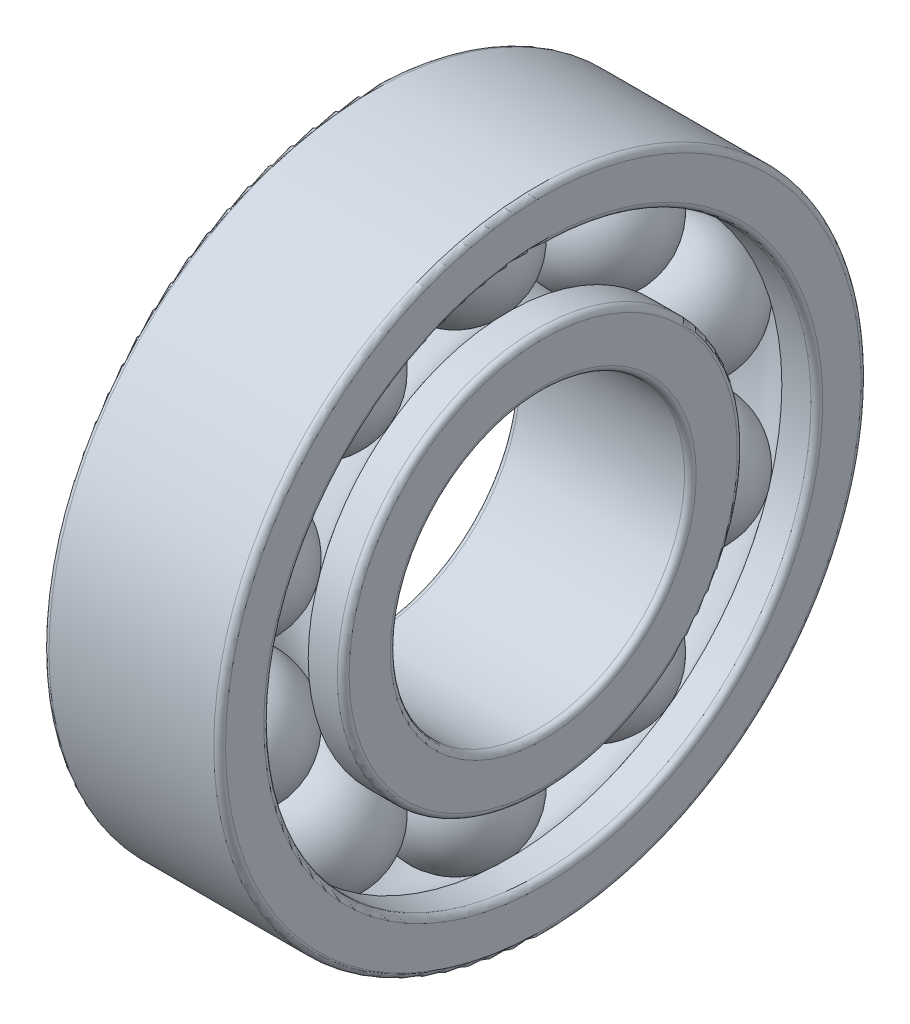
SolidWorks part; units mm, degrees
ref_plane "Front Plane" through (0, 0, 0) normal (0, 0, 1) x (1, 0, 0)
ref_plane "Top Plane" through (0, 0, 0) normal (0, 1, 0) x (1, 0, 0)
ref_plane "Right Plane" through (0, 0, 0) normal (1, 0, 0) x (0, 0, -1)
sketch "Sketch1" plane through (0, 0, 0) normal (0, 0, 1) x (1, 0, 0)
  line L0 (-11.0577, 0) -> (10.7979, 0) construction
  line L1 (0, 2.5) -> (0, 2.925) construction
  line L2 (1.5, 2.6) -> (1.5, 3.3)
  line L3 (-1.5, 2.6) -> (-1.5, 3.3)
  line L4 (-1.4, 5.5) -> (1.4, 5.5)
  line L5 (-1.4, 4.65) -> (-0.9052, 4.65)
  line L6 (-1.4, 3.4) -> (-0.9052, 3.4)
  line L7 (-1.4, 2.5) -> (1.4, 2.5)
  line L8 (-1.5, 4.75) -> (-1.5, 5.4)
  line L9 (-1.5, 0) -> (-1.5, 5.5) construction
  line L10 (0, 5.125) -> (0, 5.5) construction
  line L11 (0, 0) -> (0, 5.5) construction
  line L12 (1.5, 4.75) -> (1.5, 5.4)
  line L13 (1.5, 0) -> (1.5, 5.5) construction
  line L14 (0.9052, 4.65) -> (1.4, 4.65)
  line L15 (0.9052, 3.4) -> (1.4, 3.4)
  arc A0 (-1.4, 4.65) -> (-1.5, 4.75) centre (-1.4, 4.75) cw
  arc A1 (1.4, 4.65) -> (1.5, 4.75) centre (1.4, 4.75) ccw
  arc A2 (1.5, 5.4) -> (1.4, 5.5) centre (1.4, 5.4) ccw
  arc A3 (-1.5, 5.4) -> (-1.4, 5.5) centre (-1.4, 5.4) cw
  arc A4 (-1.4, 2.5) -> (-1.5, 2.6) centre (-1.4, 2.6) cw
  arc A5 (1.4, 2.5) -> (1.5, 2.6) centre (1.4, 2.6) ccw
  arc A6 (1.4, 3.4) -> (1.5, 3.3) centre (1.4, 3.3) cw
  arc A7 (-1.4, 3.4) -> (-1.5, 3.3) centre (-1.4, 3.3) ccw
  arc A8 (-0.9052, 3.4) -> (0.9052, 3.4) centre (0, 4.025) ccw
  arc A9 (0.9052, 4.65) -> (-0.9052, 4.65) centre (0, 4.025) ccw
  point P20 (-1.5, 4.65)
  point P23 (1.5, 4.65)
  dimension "D1" = 0.1
  dimension "D4" = 2.2
  dimension "D5" = 4.65
  dimension "D6" = 3.4
  dimension "D7" = 2.5
  dimension "D2" = 1.5
  dimension "D3" = 1.5
revolve "Revolve1" add sketch "Sketch1" angle 360 about L0
sketch "Sketch2" plane through (0, 0, 0) normal (0, 0, 1) x (1, 0, 0)
  line L0 (0, 2.925) -> (0, 5.125)
  arc A0 (0, 2.925) -> (0, 5.125) centre (0, 4.025) ccw
revolve "Revolve2" add sketch "Sketch2" angle 360 about L0
pattern_circular "CirPattern1" count 10 over 360 about axis through (0, 0, 0) along (1, 0, 0) of bodies 103
